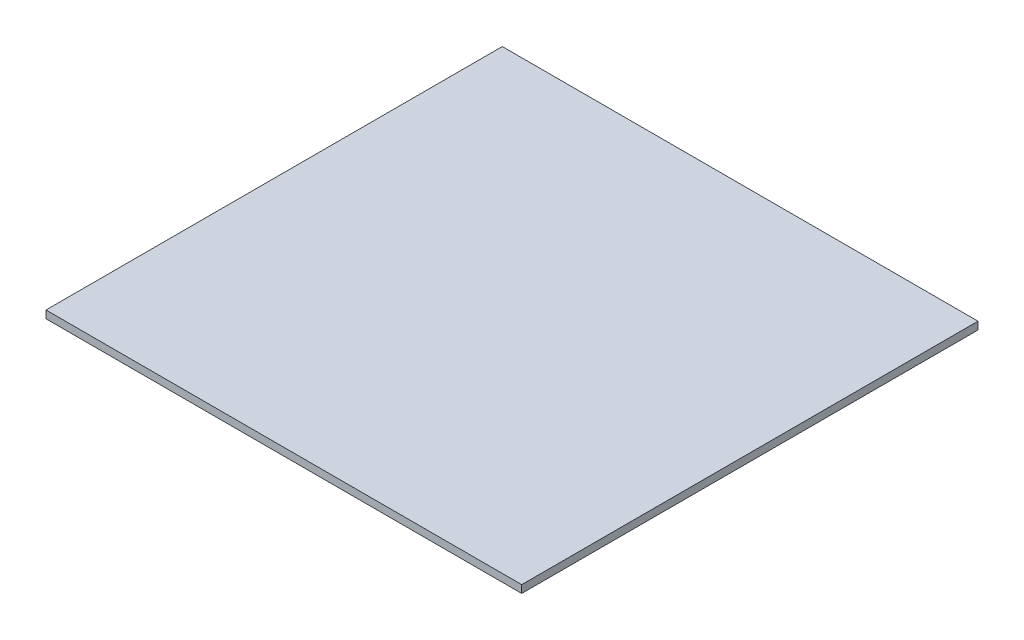
SolidWorks part; units mm, degrees
material "A-Glass Fiber"
ref_plane "Front Plane" through (0, 0, 0) normal (0, 0, 1) x (1, 0, 0)
ref_plane "Top Plane" through (0, 0, 0) normal (0, 1, 0) x (1, 0, 0)
ref_plane "Right Plane" through (0, 0, 0) normal (1, 0, 0) x (0, 0, -1)
sketch "Sketch1" plane through (0, 0, 0) normal (0, 1, 0) x (1, 0, 0)
  line L1 (0, 0) -> (62.23, 0)
  line L2 (0, 0) -> (0, 59.69)
  line L3 (0, 59.69) -> (62.23, 59.69)
  line L4 (62.23, 0) -> (62.23, 59.69)
  dimension "D1" = 62.23
  dimension "D2" = 59.69
extrude "Boss-Extrude1" add sketch "Sketch1" along normal blind 1
